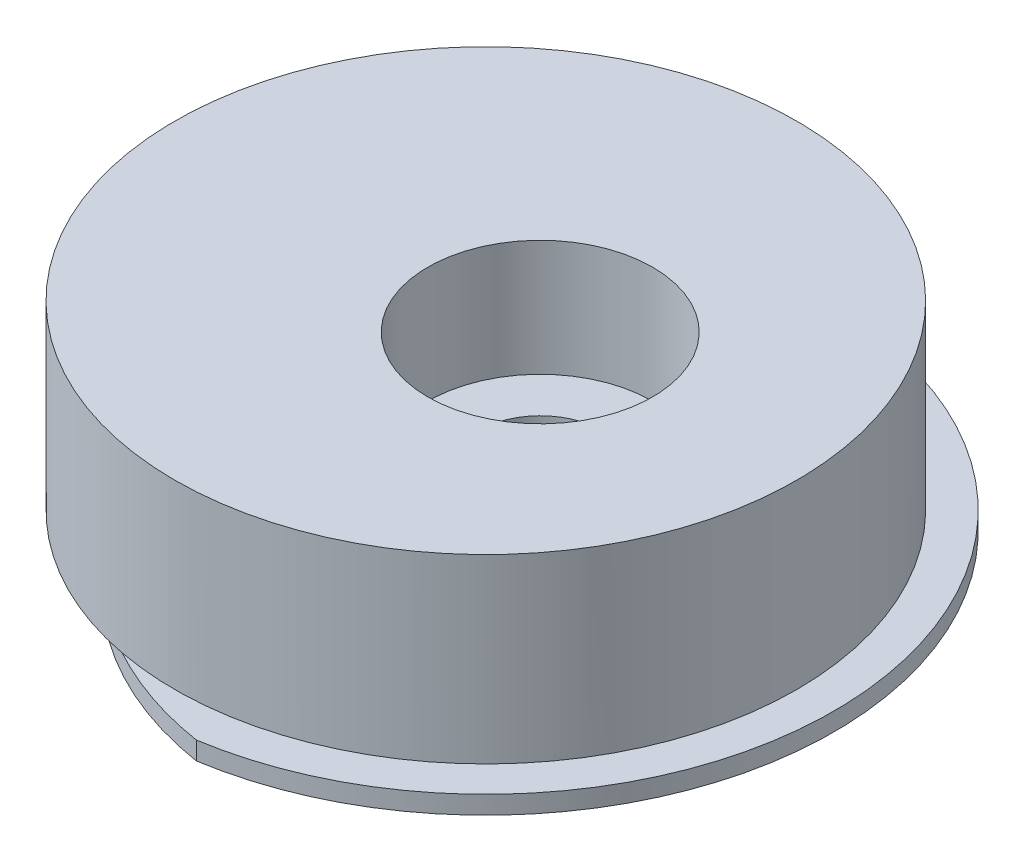
SolidWorks part; units mm, degrees
ref_plane "Front Plane" through (0, 0, 0) normal (0, 0, 1) x (1, 0, 0)
ref_plane "Top Plane" through (0, 0, 0) normal (0, 1, 0) x (1, 0, 0)
ref_plane "Right Plane" through (0, 0, 0) normal (1, 0, 0) x (0, 0, -1)
sketch "Sketch1" plane through (0, 0, 0) normal (0, 1, 0) x (1, 0, 0)
  line L0 (-3.025, 0) -> (3.025, 0) construction
  line L1 (0, -3.025) -> (0, 3.025) construction
  circle A0 centre (1.5, 0) radius 9.6
  circle A1 centre (-1.5, 0) radius 9.6
  dimension "D1" = 19.2
  dimension "D2" = 1.5
extrude "Boss-Extrude1" add sketch "Sketch1" along normal blind 0.5 contours A1 A0
sketch "Sketch2" plane through (0, 0.5, 0) normal (0, 1, 0) x (1, 0, 0)
  line L0 (-3.025, 0) -> (3.025, 0) construction
  line L1 (0, -3.025) -> (0, 3.025) construction
  circle A0 centre (-1.5, 0) radius 8.575
  dimension "D2" = 1.5
  dimension "D1" = 17.15
extrude "Boss-Extrude2" add sketch "Sketch2" along normal blind 5
sketch "Sketch3" plane through (0, 0, 0) normal (0, 1, 0) x (1, 0, 0)
  line L0 (0, -3.025) -> (0, 3.025) construction
  circle A0 centre (0, 5.8) radius 1.59
  circle A1 centre (0, -5.8) radius 1.29
  dimension "D1" = 3.18
  dimension "D3" = 2.58
  dimension "D2" = 5.8
  dimension "D4" = 5.8
extrude "Cut-Extrude1" cut sketch "Sketch3" along normal blind 4
sketch "Sketch4" plane through (0, 5.5, 0) normal (0, 1, 0) x (1, 0, 0)
  circle A0 centre (0, 0) radius 1.7
  dimension "D1" = 3.4
extrude "Cut-Extrude2" cut sketch "Sketch4" against normal through all
sketch "Sketch5" plane through (0, 5.5, 0) normal (0, 1, 0) x (1, 0, 0)
  circle A0 centre (0, 0) radius 3.1
  dimension "D1" = 6.2
extrude "Cut-Extrude3" cut sketch "Sketch5" against normal blind 3.2
equation "\"pin_circle_R\" = 27"
equation "\"ecc\" = 1.5"
equation "\"n_pins\" = 11"
equation "\"pin_d\" = 3"
equation "\"out_pin_R\" = 18.5"
equation "\"disc_clr\" = 0.1"
equation "\"seat_6803\" = 26.02"
equation "\"disc_t\" = 5"
equation "\"out_hole_clr\" = 0.7"
equation "\"boss_17\" = 17.15"
equation "\"rotor_bolt_R\" = 10"
equation "\"m25_clr\" = 2.8"
equation "\"m25_head\" = 5"
equation "\"insert_hole\" = 4.4"
equation "\"csk\" = 0.6"
equation "\"peg_d\" = 3.0"
equation "\"plug_d\" = 8.6"
equation "\"peg_clr\" = 0.18"
equation "\"m3_clr\" = 3.4"
equation "\"m3_head\" = 6.2"
equation "\"D2@Sketch1\"=\"ecc\""
equation "\"D1@Sketch2\"=\"boss_17\""
equation "\"D1@Sketch3\"=\"peg_d\"+\"peg_clr\""
equation "\"D3@Sketch3\"=\"peg_d\"-0.6+\"peg_clr\""
equation "\"D2@Sketch2\"=\"ecc\""
equation "\"D1@Sketch4\"=\"m3_clr\""
equation "\"D1@Sketch5\"=\"m3_head\""
equation "\"seat_6806\" = 42.1"
equation "\"pin_press\" = 3.2"
equation "\"pin_slip\" = 3.35"
equation "\"hub_30\" = 30.20"
equation "\"hub_short\" = 0.2"
equation "\"m3_tap\" = 2.8"
equation "\"rear_plate_t\" = 2"
equation "\"motor_ring\" = 40.4"
